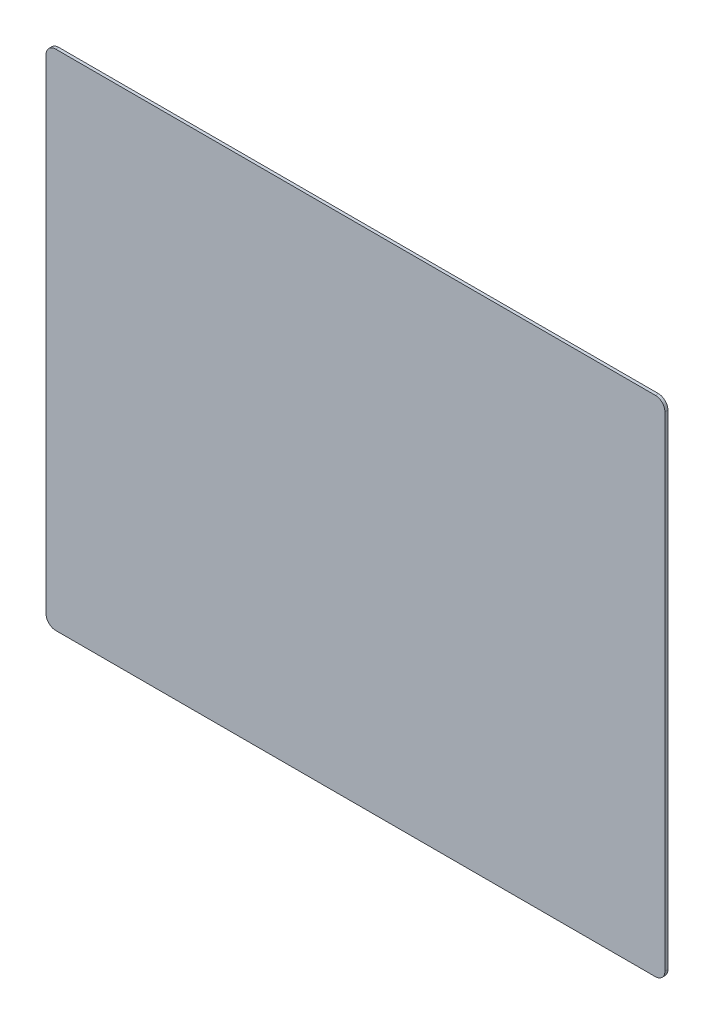
SolidWorks part; units mm, degrees
ref_plane "Front Plane" through (0, 0, 0) normal (0, 0, 1) x (1, 0, 0)
ref_plane "Top Plane" through (0, 0, 0) normal (0, 1, 0) x (1, 0, 0)
ref_plane "Right Plane" through (0, 0, 0) normal (1, 0, 0) x (0, 0, -1)
sketch "Sketch1" plane through (0, 0, 0) normal (0, 0, 1) x (1, 0, 0)
  line L1 (-476.498, 137.4676) -> (171.202, 137.4676)
  line L2 (-476.498, 137.4676) -> (-476.498, -389.5084)
  line L3 (-476.498, -389.5084) -> (171.202, -389.5084)
  line L4 (171.202, 137.4676) -> (171.202, -389.5084)
  dimension "D1" = 647.7
  dimension "D2" = 526.976
extrude "Boss-Extrude1" add sketch "Sketch1" along normal blind 3.175 contours L1 L4 L3 L2
fillet "Fillet1" radius 10 4 edges at (171.202, -389.5084, 1.5875) (-476.498, -389.5084, 1.5875) (-476.498, 137.4676, 1.5875) (171.202, 137.4676, 1.5875)
